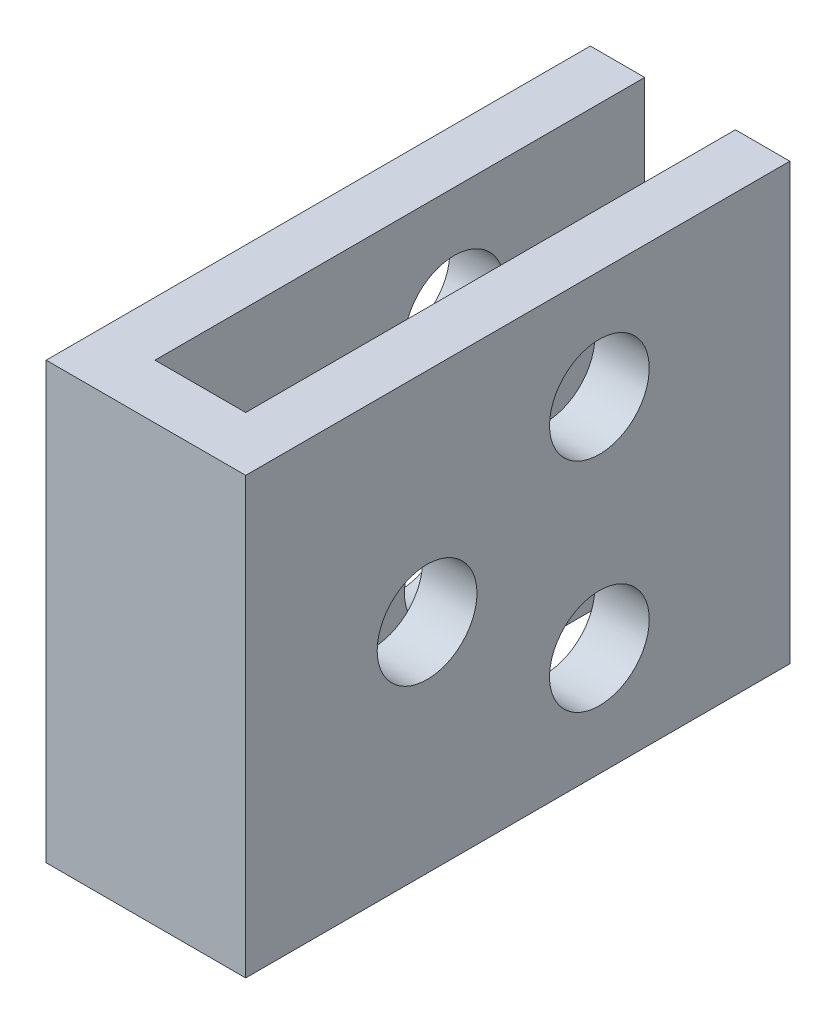
SolidWorks part; units mm, degrees
material "A6061"
ref_plane "前视基准面" through (0, 0, 0) normal (0, 0, 1) x (1, 0, 0)
ref_plane "上视基准面" through (0, 0, 0) normal (0, 1, 0) x (1, 0, 0)
ref_plane "右视基准面" through (0, 0, 0) normal (1, 0, 0) x (0, 0, -1)
sketch "草图1" plane through (0, 0, 0) normal (0, 1, 0) x (1, 0, 0)
  line L0 (0, 18.993) -> (0, -12.9662) construction
  line L1 (5.5, 0) -> (-5.5, 0)
  line L2 (-5.5, 0) -> (-5.5, 30)
  line L3 (-5.5, 30) -> (-2.5, 30)
  line L4 (-2.5, 30) -> (-2.5, 3)
  line L5 (-2.5, 3) -> (2.5, 3)
  line L6 (2.5, 30) -> (2.5, 3)
  line L7 (5.5, 30) -> (2.5, 30)
  line L8 (5.5, 0) -> (5.5, 30)
  point P10 (0, 3)
  point P13 (0, 0)
  dimension "D1" = 3
  dimension "D2" = 11
  dimension "D3" = 3
  dimension "D4" = 30
extrude "凸台-拉伸1" add sketch "草图1" along normal mid plane 24
sketch "草图5" plane through (-5.5, 0, 0) normal (-1, 0, 0) x (0, 0, 1)
  line L0 (2.1554, 0) -> (-16.368, 0) construction
  line L1 (0, 12) -> (0, -12) construction
  circle A0 centre (-10, 0) radius 2.75
  circle A1 centre (-19.5, 6) radius 2.75
  circle A2 centre (-19.5, -6) radius 2.75
  dimension "D1" = 5.5
  dimension "D2" = 10
  dimension "D3" = 5.5
  dimension "D4" = 12
  dimension "D5" = 9.5
extrude "切除-拉伸1" cut sketch "草图5" against normal through all
